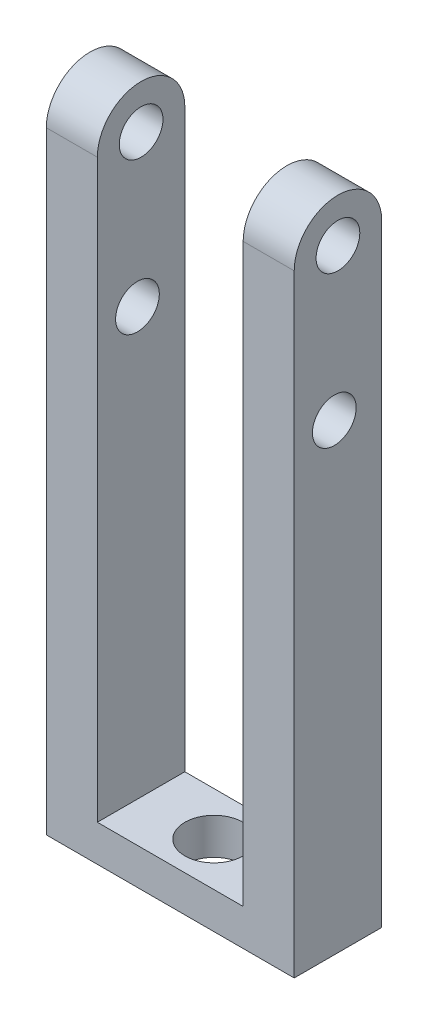
SolidWorks part; units mm, degrees
material "Plain Carbon Steel"
ref_plane "Front Plane" through (0, 0, 0) normal (0, 0, 1) x (1, 0, 0)
ref_plane "Top Plane" through (0, 0, 0) normal (0, 1, 0) x (1, 0, 0)
ref_plane "Right Plane" through (0, 0, 0) normal (1, 0, 0) x (0, 0, -1)
sketch "Sketch1" plane through (0, 0, 0) normal (0, 1, 0) x (1, 0, 0)
  line L1 (-17, -6) -> (17, -6)
  line L2 (-17, -6) -> (-17, 6)
  line L3 (-17, 6) -> (17, 6)
  line L4 (17, -6) -> (17, 6)
  line L5 (0, 6) -> (0, -6) construction
  line L6 (-17, 0) -> (17, 0) construction
  point P1 (0, 0)
  dimension "D1" = 12
  dimension "D2" = 34
extrude "Boss-Extrude1" add sketch "Sketch1" along normal blind 5
sketch "Sketch3" plane through (0, 0, 0) normal (1, 0, 0) x (0, 0, -1)
  line L0 (0, 0) -> (0, 16.3575) construction
sketch3d "3DSketch1" plane through (0, 0, 0) normal (0, 0, 1) x (1, 0, 0)
  dimension "D1" = 17
sketch "Sketch5" plane through (17, 0, 0) normal (1, 0, 0) x (0, 0, -1)
  line L0 (6.6, 0) -> (-6.6, 0) construction
  line L1 (-6, 5) -> (6, 5)
  line L2 (-6, 5) -> (-6, 84)
  line L4 (6, 5) -> (6, 84)
  arc A0 (-6, 84) -> (6, 84) centre (0, 84) cw
  circle A1 centre (0, 84) radius 3
  circle A2 centre (-0.5, 63.5) radius 3
  dimension "D2" = 6
  dimension "D3" = 6
  dimension "D1" = 84
  dimension "D4" = 63.5
  dimension "D5" = 12
extrude "Boss-Extrude3" add sketch "Sketch5" against normal blind 7
sketch "Sketch6" plane through (0, 5, 0) normal (0, 1, 0) x (1, 0, 0)
  circle A0 centre (0, 0) radius 1.5
  dimension "D1" = 3
extrude "Cut-Extrude1" cut sketch "Sketch6" against normal blind 3
sketch "Sketch7" plane through (10, 0, 0) normal (-1, 0, 0) x (0, 0, 1)
  circle A0 centre (0, 84) radius 4
  dimension "D1" = 8
sketch "Sketch8" plane through (0, 5, 0) normal (0, 1, 0) x (1, 0, 0)
  circle A0 centre (0, 0) radius 4
  dimension "D1" = 8
extrude "Cut-Extrude4" cut sketch "Sketch8" against normal through all
mirror "Mirror1" about plane through (0, 0, 0) normal (1, 0, 0) of "Boss-Extrude3"
